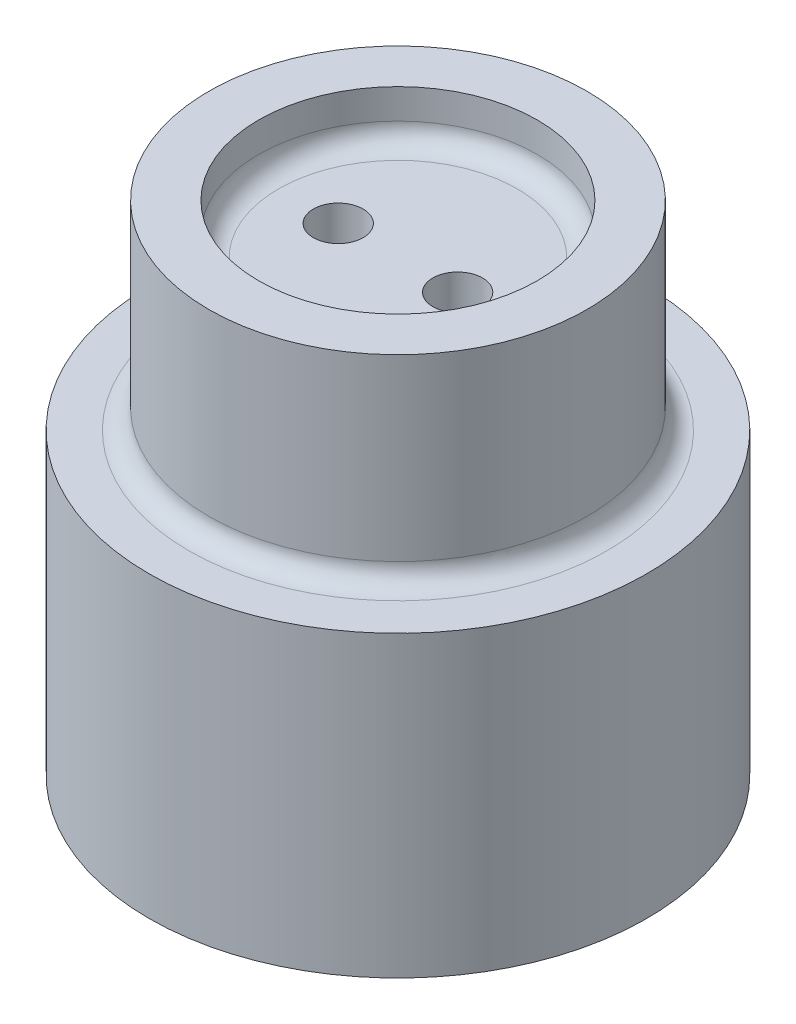
SolidWorks part; units mm, degrees
ref_plane "Front Plane" through (0, 0, 0) normal (0, 0, 1) x (1, 0, 0)
ref_plane "Top Plane" through (0, 0, 0) normal (0, 1, 0) x (1, 0, 0)
ref_plane "Right Plane" through (0, 0, 0) normal (1, 0, 0) x (0, 0, -1)
sketch "Sketch1" plane through (0, 0, 0) normal (0, 0, 1) x (1, 0, 0)
  line L0 (0, 0) -> (63.5, 0)
  line L1 (63.5, 0) -> (63.5, 76.2)
  line L2 (63.5, 76.2) -> (48.26, 76.2)
  line L3 (48.26, 76.2) -> (48.26, 127)
  line L6 (0, 12.7) -> (50.8, 12.7)
  line L7 (50.8, 12.7) -> (50.8, 63.5)
  line L8 (50.8, 63.5) -> (35.56, 63.5)
  line L9 (35.56, 63.5) -> (35.56, 127)
  line L10 (35.56, 127) -> (48.26, 127)
  line L11 (0, 12.7) -> (0, 0)
  dimension "D1" = 63.5
  dimension "D2" = 76.2
  dimension "D3" = 15.24
  dimension "D4" = 50.8
  dimension "D5" = 12.7
revolve "Revolve2" add sketch "Sketch1" angle 360 about L11
ref_plane "Plane1" through (0, 114.3, 0) normal (0, 1, 0) x (1, 0, 0)
sketch "Sketch2" plane through (0, 114.3, 0) normal (0, 1, 0) x (1, 0, 0)
  circle A0 centre (0, 0) radius 35.56
  circle A1 centre (0, 0) radius 35.56 construction
extrude "Boss-Extrude1" add sketch "Sketch2" against normal blind 7.62
sketch "Sketch4" plane through (0, 114.3, 0) normal (0, 1, 0) x (1, 0, 0)
  circle A0 centre (15.24, 0) radius 6.35
  circle A1 centre (15.24, 0) radius 8.89
  point P2 (0, 0)
  point P4 (15.24, 0)
  point P5 (0, 0)
  dimension "D2" = 12.7
  dimension "D1" = 15.24
  dimension "D3" = 2.54
ref_plane "Plane3" through (0, 0, 0) normal (0, 0, 1) x (1, 0, 0)
sketch "Sketch5" plane through (0, 0, 0) normal (0, 0, 1) x (1, 0, 0)
  line L0 (15.24, 114.3) -> (15.24, 50.8)
  line L1 (21.59, 114.3) -> (8.89, 114.3) construction
  line L2 (15.24, 50.8) -> (33.02, 50.8)
  line L3 (33.02, 50.8) -> (33.02, 0)
  line L4 (-63.5, 0) -> (63.5, 0) construction
  dimension "D1" = 63.5
  dimension "D2" = 17.78
sweep "Sweep1" add profiles "Sketch4" path "Sketch5"
sketch "Sketch7" plane through (0, 0, 0) normal (0, -1, 0) x (1, 0, 0)
  line L0 (69.85, 0) -> (-69.85, 0) construction
  circle A0 centre (33.02, 0) radius 6.35
  circle A1 centre (33.02, 0) radius 6.35 construction
extrude "Cut-Extrude1" cut sketch "Sketch7" against normal up to next
sketch "Sketch8" plane through (0, 114.3, 0) normal (0, 1, 0) x (1, 0, 0)
  circle A0 centre (15.24, 0) radius 6.35
  circle A1 centre (15.24, 0) radius 6.35 construction
extrude "Cut-Extrude2" cut sketch "Sketch8" against normal up to next
mirror "Mirror1" about plane through (0, 0, 0) normal (1, 0, 0) of "Sweep1", "Cut-Extrude1", "Cut-Extrude2"
fillet "Fillet1" radius 5.08 2 edges at (0, 76.2, 48.26) (0, 114.3, 35.56)
